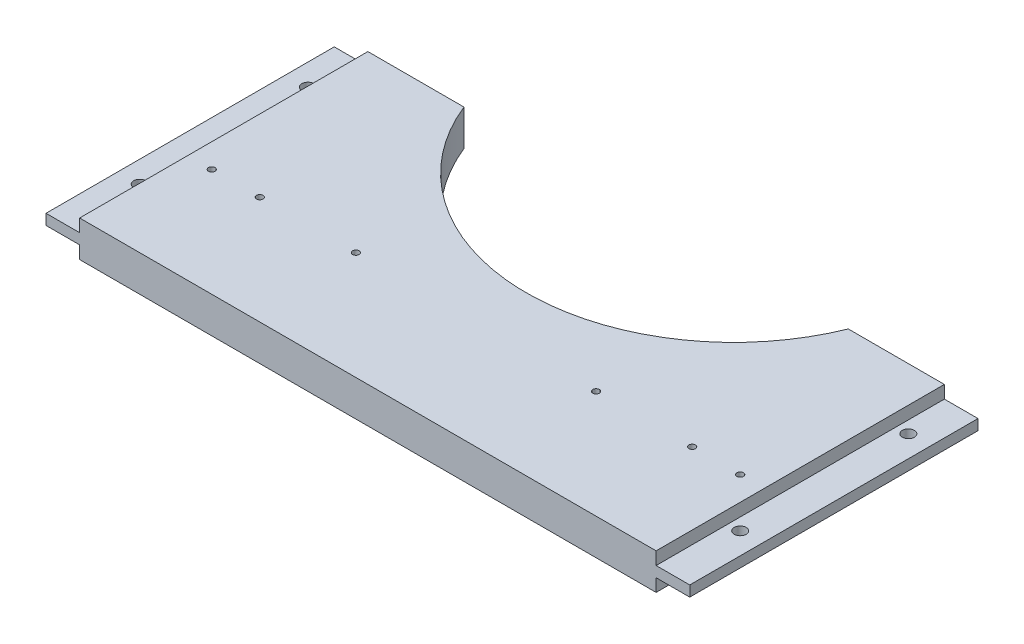
SolidWorks part; units mm, degrees
ref_plane "Front" through (0, 0, 0) normal (0, 0, 1) x (1, 0, 0)
ref_plane "Top" through (0, 0, 0) normal (0, 1, 0) x (1, 0, 0)
ref_plane "Right" through (0, 0, 0) normal (1, 0, 0) x (0, 0, -1)
sketch "Sketch1" plane through (0, 0, 0) normal (0, 1, 0) x (1, 0, 0)
  line L0 (-101.6, 76.2) -> (-152.4, 76.2)
  line L5 (-152.4, 76.2) -> (-152.4, -76.2)
  line L6 (-152.4, -76.2) -> (152.4, -76.2)
  line L7 (152.4, -76.2) -> (152.4, 76.2)
  line L8 (152.4, 76.2) -> (101.6, 76.2)
  line L9 (0, -50) -> (0, 50) construction
  line L10 (-24.4982, 7.62) -> (79.6476, 7.62) construction
  line L11 (-50, 0) -> (50, 0) construction
  circle A0 centre (0, 117.1693) radius 109.5493
  point P5 (152.4, 0)
  point P11 (0, -76.2)
  dimension "D1" = 152.4
  dimension "D2" = 83.82
  dimension "D3" = 50.8
  dimension "D4" = 304.8
extrude "Boss-Extrude1" add sketch "Sketch1" along normal mid plane 19.05 contours L5 L10 A0 L0 | L10 L5 L6 L7 | A0 L10 L7 L8
sketch "Sketch2" plane through (0, 9.525, 0) normal (0, 1, 0) x (1, 0, 0)
  line L0 (-152.4, -19.05) -> (152.4, -19.05) construction
  line L1 (-152.4, 76.2) -> (-152.4, -76.2) construction
  line L2 (152.4, -76.2) -> (152.4, 76.2) construction
  line L3 (-152.4, -76.2) -> (152.4, -76.2) construction
  point P8 (-139.7, -19.05)
  point P9 (-114.3, -19.05)
  point P10 (-63.5, -19.05)
  dimension "D1" = 57.15
  dimension "D2" = 12.7
  dimension "D3" = 25.4
  dimension "D4" = 50.8
hole_wizard "#8-32 Tapped Hole1" positions "Sketch3" profile "Sketch5" tap size "#8-32" standard "ANSI Inch" end condition through all
sketch "Sketch3" plane through (0, 9.525, 0) normal (0, 1, 0) x (1, 0, 0)
  point P0 (-139.7, -19.05)
  point P3 (-114.3, -19.05)
  point P6 (-63.5, -19.05)
sketch "Sketch5" plane through (-139.7, 9.525, 19.05) normal (1, 0, 0) x (0, 0, 1)
  line L0 (0, 0) -> (0, 19.05)
  line L1 (0, 19.05) -> (1.7272, 19.05)
  line L2 (1.7272, 19.05) -> (1.7272, 0)
  line L5 (1.7272, 0) -> (0, 0)
  line L11 (0, -6.35) -> (0, 107.95) construction
  dimension "Thru Tap Drill Dia." = 3.4544
  dimension "Thru Tap Drill Depth" = 19.05
cosmetic thread "Hole Thread1" parameters "D2"=4.1656
cosmetic thread "Hole Thread2" parameters "D2"=4.1656
cosmetic thread "Hole Thread3" parameters "D2"=4.1656
mirror "Mirror1" about plane through (0, 0, 0) normal (1, 0, 0) of "#8-32 Tapped Hole1"
cosmetic thread "Hole Thread4" parameters "D2"=4.1656
cosmetic thread "Hole Thread5" parameters "D2"=4.1656
cosmetic thread "Hole Thread6" parameters "D2"=4.1656
sketch "Sketch6" plane through (0, 0, 0) normal (0, 1, 0) x (1, 0, 0)
  line L0 (-152.4, -76.2) -> (152.4, -76.2) construction
  line L1 (-152.4, 76.2) -> (-170.18, 76.2)
  line L2 (-152.4, 76.2) -> (-152.4, -76.2)
  line L3 (-152.4, -76.2) -> (-170.18, -76.2)
  line L4 (-170.18, 76.2) -> (-170.18, -76.2)
  dimension "D1" = 17.78
extrude "Boss-Extrude2" add sketch "Sketch6" along normal mid plane 5.588
sketch "Sketch7" plane through (0, 2.794, 0) normal (0, 1, 0) x (1, 0, 0)
  line L1 (-152.4, 76.2) -> (-170.18, 76.2) construction
  line L2 (-170.18, -76.2) -> (-152.4, -76.2) construction
  line L3 (-152.4, 76.2) -> (-152.4, -76.2) construction
  point P0 (-158.75, 50.8)
  point P1 (-158.75, -38.1)
  dimension "D1" = 25.4
  dimension "D2" = 38.1
  dimension "D3" = 6.35
hole_wizard "1/4 (0.25) Diameter Hole1" positions "Sketch8" profile "Sketch10" hole size "1/4" standard "ANSI Inch" end condition through all
sketch "Sketch8" plane through (0, 2.794, 0) normal (0, 1, 0) x (1, 0, 0)
  point P0 (-158.75, 50.8)
  point P3 (-158.75, -38.1)
sketch "Sketch10" plane through (-158.75, 2.794, -50.8) normal (1, 0, 0) x (0, 0, 1)
  line L0 (0, 0) -> (0, 12.319)
  line L1 (0, 12.319) -> (3.175, 12.319)
  line L2 (3.175, 12.319) -> (3.175, 0)
  line L5 (3.175, 0) -> (0, 0)
  line L11 (0, -6.35) -> (0, 107.95) construction
  dimension "Thru Hole Dia." = 6.35
  dimension "Thru Hole Depth" = 12.319
mirror "Mirror2" about plane through (0, 0, 0) normal (1, 0, 0) of "1/4 (0.25) Diameter Hole1", "Boss-Extrude2"
